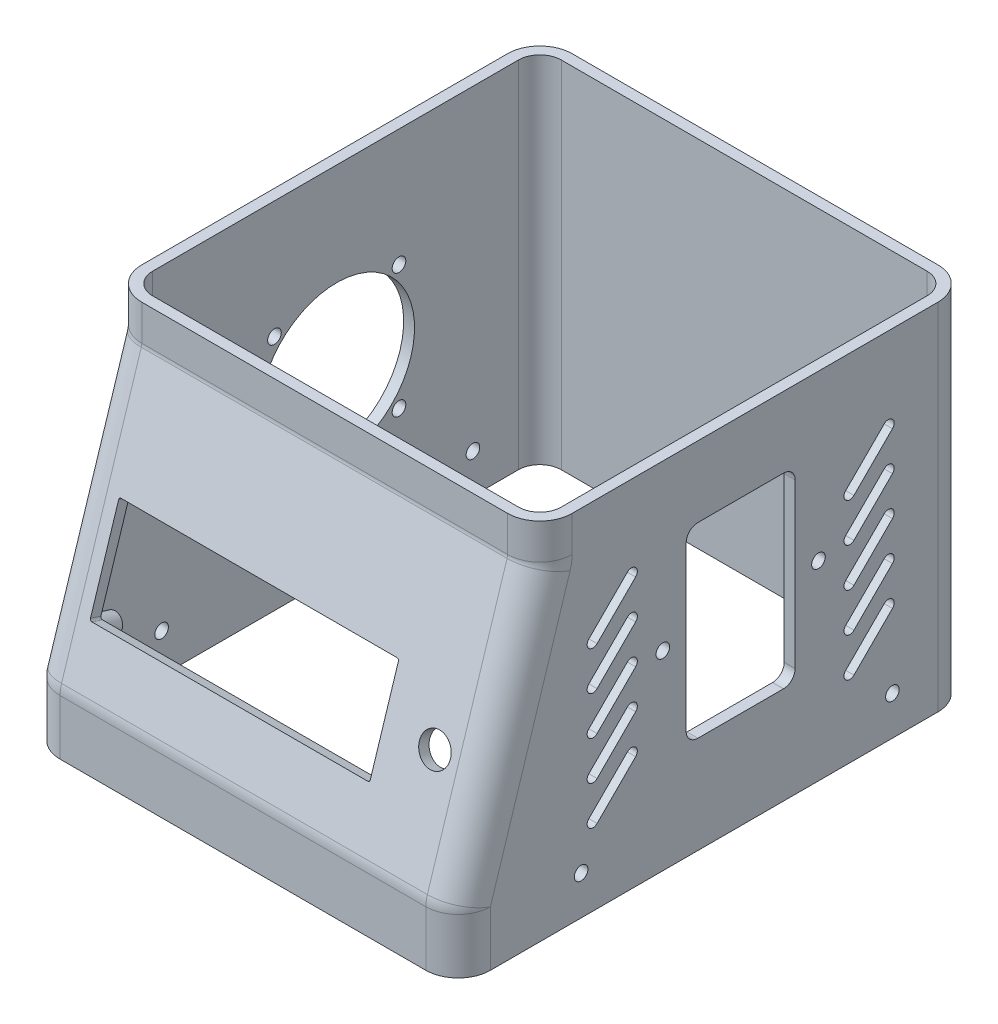
SolidWorks part; units mm, degrees
ref_plane "Front Plane" through (0, 0, 0) normal (0, 0, 1) x (1, 0, 0)
ref_plane "Top Plane" through (0, 0, 0) normal (0, 1, 0) x (1, 0, 0)
ref_plane "Right Plane" through (0, 0, 0) normal (1, 0, 0) x (0, 0, -1)
sketch "Sketch4" plane through (0, 0, 0) normal (1, 0, 0) x (0, 0, -1)
  line L0 (0, 0) -> (0, 15)
  line L1 (0, 15) -> (21, 81.2)
  line L2 (21, 81.2) -> (21, 91.2)
  line L3 (21, 91.2) -> (126, 91.2)
  line L4 (126, 91.2) -> (126, 0)
  line L5 (126, 0) -> (0, 0)
  dimension "D1" = 15
  dimension "D2" = 17.6
  dimension "D3" = 10
  dimension "D4" = 91.2
  dimension "D5" = 69.451
  dimension "D6" = 105
  dimension "D7" = 126
extrude "Boss-Extrude3" add sketch "Sketch4" along normal mid plane 105
fillet "Fillet3" radius 5.5 10 edges at (-52.5, 86.2, -21) (0, 81.2, -21) (52.5, 48.1, -10.5) (0, 15, 0) (-52.5, 48.1, -10.5) (-52.5, 7.5, 0) (52.5, 7.5, 0) (-52.5, 45.6, -126) (52.5, 45.6, -126) (52.5, 86.2, -21)
shell "Shell1" thickness 2.8
ref_plane "Plane1" through (0, 0, -73.5) normal (0, 0, 1) x (1, 0, 0)
sketch "Sketch6" plane through (0, 1.3714, 4.3233) normal (0, -0.3024, -0.9532) x (-1, 0, 0)
  line L0 (-27.45, 54.0493) -> (43.45, 54.0493)
  line L5 (-27.95, 53.5493) -> (-27.95, 29.6493)
  line L6 (-27.45, 29.1493) -> (43.45, 29.1493)
  line L7 (43.95, 53.5493) -> (43.95, 29.6493)
  line L8 (47, 15.1493) -> (-47, 15.1493) construction
  line L9 (-29.5, 57.5993) -> (45.5, 57.5993) construction
  line L10 (-29.5, 57.5993) -> (-29.5, 26.5993) construction
  line L11 (-29.5, 26.5993) -> (45.5, 26.5993) construction
  line L12 (45.5, 57.5993) -> (45.5, 26.5993) construction
  line L14 (47, 82.8974) -> (47, 15.1493) construction
  arc A0 (-27.95, 29.6493) -> (-27.45, 29.1493) centre (-27.45, 29.6493) ccw
  arc A1 (43.45, 29.1493) -> (43.95, 29.6493) centre (43.45, 29.6493) ccw
  arc A2 (43.95, 53.5493) -> (43.45, 54.0493) centre (43.45, 53.5493) ccw
  arc A3 (-27.45, 54.0493) -> (-27.95, 53.5493) centre (-27.45, 53.5493) ccw
  circle A4 centre (-29.5, 57.5993) radius 1.5 construction
  circle A5 centre (45.5, 57.5993) radius 1.5 construction
  circle A6 centre (45.5, 26.5993) radius 1.5 construction
  circle A7 centre (-29.5, 26.5993) radius 1.5 construction
  dimension "D3" = 0.5
  dimension "D10" = 3
  dimension "D1" = 14
  dimension "D2" = 1.5
  dimension "D4" = 24.9
  dimension "D5" = 71.9
  dimension "D6" = 75
  dimension "D7" = 31
  dimension "D8" = 3.55
  dimension "D9" = 3.1
  dimension "D11" = 3.55
  dimension "D12" = 2.55
extrude "Cut-Extrude1" cut sketch "Sketch6" against normal up to next
sketch "Sketch7" plane through (0, 1.3714, 4.3233) normal (0, -0.3024, -0.9532) x (-1, 0, 0)
  circle A4 centre (-29.5, 57.5993) radius 1.25
  circle A5 centre (-29.5, 26.5993) radius 1.25
  circle A6 centre (45.5, 26.5993) radius 1.25
  circle A7 centre (45.5, 57.5993) radius 1.25
  circle A8 centre (-29.5, 57.5993) radius 2.5
  circle A9 centre (45.5, 57.5993) radius 2.5
  circle A10 centre (45.5, 26.5993) radius 2.5
  circle A11 centre (-29.5, 26.5993) radius 2.5
  dimension "D1" = 5
  dimension "D2" = 2.5
extrude "Boss-Extrude4" add sketch "Sketch7" along normal offset from surface (5.7 mm away) 8.5 up to face at (-8, 41.8701, -5.5862)
sketch "Sketch8" plane through (0, 2.2181, 6.9922) normal (0, 0.3024, 0.9532) x (1, 0, 0)
  line L0 (27.95, 41.5993) -> (40.95, 41.5993) construction
  line L1 (27.95, 29.6493) -> (27.95, 53.5493) construction
  circle A0 centre (40.95, 41.5993) radius 4
  dimension "D1" = 8
  dimension "D2" = 13
extrude "Cut-Extrude2" cut sketch "Sketch8" against normal up to next
sketch "Sketch9" plane through (0, 0, -126) normal (0, 0, 1) x (1, 0, 0)
  line L0 (0, 0) -> (0, 91.2) construction
  line L1 (-40, 71) -> (22, 71) construction
  line L2 (-40, 71) -> (-40, 19) construction
  line L3 (-40, 19) -> (22, 19) construction
  line L4 (22, 71) -> (22, 19) construction
  line L5 (-44, 75) -> (26, 75)
  line L6 (-44, 75) -> (-44, 15)
  line L7 (-44, 15) -> (26, 15)
  line L8 (26, 75) -> (26, 15)
  line L9 (47, 0) -> (-47, 0) construction
  line L10 (47, 91.2) -> (-47, 91.2) construction
  dimension "D1" = 62
  dimension "D2" = 52
  dimension "D3" = 4
  dimension "D4" = 4
  dimension "D5" = 70
  dimension "D6" = 60
  dimension "D7" = 15
  dimension "D8" = 22
sketch "Sketch10" plane through (0, 0, -126) normal (0, 0, 1) x (1, 0, 0)
  circle A0 centre (-40, 19) radius 3
  circle A1 centre (-40, 71) radius 3
  circle A2 centre (22, 19) radius 3
  circle A3 centre (22, 71) radius 3
  circle A4 centre (-40, 19) radius 1.25
  circle A5 centre (-40, 71) radius 1.25
  circle A6 centre (22, 71) radius 1.25
  circle A7 centre (22, 19) radius 1.25
  dimension "D1" = 6
  dimension "D2" = 2.5
extrude "Boss-Extrude5" [suppressed] add sketch "Sketch10" along normal blind 7
sketch "Sketch11" plane through (-55.3, 0, 0) normal (-1, 0, 0) x (0, 0, 1)
  line L0 (-108.8, 10) -> (-28.8, 10) construction
  line L1 (-68.8, 10) -> (-68.8, 0) construction
  line L2 (-5.5, 0) -> (-120.5, 0) construction
  line L3 (-128.8, 0) -> (-128.8, 91.2) construction
  circle A0 centre (-108.8, 10) radius 1.75
  circle A1 centre (-28.8, 10) radius 1.75
  dimension "D1" = 3.5
  dimension "D2" = 80
  dimension "D3" = 60
  dimension "D4" = 10
extrude "Cut-Extrude3" cut sketch "Sketch11" against normal through all
chamfer "Chamfer1" [suppressed] distance 4 angle 45
sketch "Sketch12" plane through (55.3, 0, 0) normal (1, 0, 0) x (0, 0, -1)
  line L0 (5.5, 0) -> (120.5, 0) construction
  line L1 (55.8, 73) -> (83.8, 73)
  line L2 (55.8, 73) -> (55.8, 25)
  line L3 (55.8, 25) -> (83.8, 25)
  line L4 (83.8, 73) -> (83.8, 25)
  line L5 (128.8, 91.2) -> (128.8, 0) construction
  line L6 (69.8, 73) -> (69.8, 49) construction
  line L7 (69.8, 49) -> (55.8, 49) construction
  circle A0 centre (49.8, 49) radius 1.75
  circle A1 centre (89.8, 49) radius 1.75
  dimension "D5" = 40
  dimension "D6" = 3.5
  dimension "D1" = 25
  dimension "D2" = 45
  dimension "D3" = 28
  dimension "D4" = 48
extrude "Cut-Extrude4" cut sketch "Sketch12" against normal up to surface (2.8 mm away) up to face at (52.5, 10, -107.05)
ref_plane "Plane2" through (0, 79.2, 0) normal (0, 1, 0) x (1, 0, 0)
sketch "Sketch13" [suppressed] plane through (0, 78, 0) normal (0, 1, 0) x (1, 0, 0)
  line L0 (-47, 126) -> (47, 126)
  line L1 (-47, 126) -> (47, 126)
  line L2 (52.5, 120.5) -> (52.5, 26.5)
  line L3 (52.5, 120.5) -> (52.5, 26.5)
  line L4 (47, 21) -> (-47, 21)
  line L5 (47, 21) -> (-47, 21)
  line L6 (-52.5, 120.5) -> (-52.5, 26.5)
  line L7 (-52.5, 120.5) -> (-52.5, 26.5)
  line L8 (47, 26) -> (-47, 26)
  line L9 (-47.5, 120.5) -> (-47.5, 26.5)
  line L10 (-47, 121) -> (47, 121)
  line L11 (47.5, 120.5) -> (47.5, 26.5)
  line L12 (22, 126) -> (-40, 126)
  line L13 (-40, 126) -> (22, 126)
  line L15 (-40, 126) -> (22, 126)
  line L16 (22, 126) -> (-40, 126)
  arc A0 (52.5, 120.5) -> (47, 126) centre (47, 120.5) ccw
  arc A1 (52.5, 120.5) -> (47, 126) centre (47, 120.5) ccw
  arc A2 (47, 21) -> (52.5, 26.5) centre (47, 26.5) ccw
  arc A3 (47, 21) -> (52.5, 26.5) centre (47, 26.5) ccw
  arc A4 (-52.5, 26.5) -> (-47, 21) centre (-47, 26.5) ccw
  arc A5 (-52.5, 26.5) -> (-47, 21) centre (-47, 26.5) ccw
  arc A6 (-47, 126) -> (-52.5, 120.5) centre (-47, 120.5) ccw
  arc A7 (-47, 126) -> (-52.5, 120.5) centre (-47, 120.5) ccw
  arc A8 (-47.5, 26.5) -> (-47, 26) centre (-47, 26.5) ccw
  arc A9 (-47, 121) -> (-47.5, 120.5) centre (-47, 120.5) ccw
  arc A10 (47.5, 120.5) -> (47, 121) centre (47, 120.5) ccw
  arc A11 (47, 26) -> (47.5, 26.5) centre (47, 26.5) ccw
  dimension "D1" = 5
extrude "Boss-Extrude6" [suppressed] add sketch "Sketch13" against normal blind 3.5
chamfer "Chamfer2" [suppressed] distance 5 angle 60
sketch "Sketch15" [suppressed] plane through (0, 88, 0) normal (0, 1, 0) x (1, 0, 0)
  line L0 (0, 0) -> (0, 21) construction
  line L1 (-52.5, 78.5) -> (-5, 78.5)
  line L2 (-52.5, 78.5) -> (-52.5, 68.5)
  line L3 (-52.5, 68.5) -> (-5, 68.5)
  line L4 (52.5, 78.5) -> (52.5, 68.5)
  line L5 (-5, 126) -> (5, 126)
  line L6 (-5, 126) -> (-5, 78.5)
  line L7 (-5, 21) -> (5, 21)
  line L8 (5, 126) -> (5, 78.5)
  line L9 (52.5, 73.5) -> (-47.5, 73.5) construction
  line L10 (-47.5, 120.5) -> (-47.5, 26.5) construction
  line L14 (-5, 68.5) -> (-5, 21)
  line L15 (5, 78.5) -> (52.5, 78.5)
  line L16 (5, 68.5) -> (5, 21)
  line L17 (5, 68.5) -> (52.5, 68.5)
  line L18 (-52.5, 120.5) -> (-52.5, 26.5) construction
  line L19 (47, 126) -> (-47, 126) construction
  line L20 (52.5, 26.5) -> (52.5, 120.5) construction
  line L21 (52.5, 120.5) -> (52.5, 26.5) construction
  line L22 (-47, 21) -> (47, 21) construction
  point P41 (52.5, 73.5)
  dimension "D1" = 10
extrude "Cut-Extrude5" [suppressed] cut sketch "Sketch15" against normal blind 2
sketch "Sketch17" plane through (0, 1.3714, 4.3233) normal (0, -0.3024, -0.9532) x (-1, 0, 0)
  line L0 (-40.95, 41.5993) -> (-40.95, 61.5993) construction
  line L1 (-40.95, 41.5993) -> (-40.95, 29.5993) construction
  circle A0 centre (-40.95, 61.5993) radius 2.5
  circle A1 centre (-40.95, 29.5993) radius 2.5
  circle A2 centre (-40.95, 61.5993) radius 1.25
  circle A3 centre (-40.95, 29.5993) radius 1.25
  circle A6 centre (-29.5, 26.5993) radius 2.5 construction
  circle A7 centre (-29.5, 26.5993) radius 1.25 construction
  dimension "D1" = 32
  dimension "D2" = 12
extrude "Boss-Extrude7" add sketch "Sketch17" along normal blind 8.4
fillet "Fillet4" radius 3 4 edges at (53.9, 73, -55.8) (53.9, 73, -83.8) (53.9, 25, -83.8) (53.9, 25, -55.8)
sketch "Sketch18" plane through (-55.3, 0, 0) normal (-1, 0, 0) x (0, 0, 1)
  line L0 (-5.5, 0) -> (-120.5, 0) construction
  line L1 (-89.8, 29) -> (-57.8, 29) construction
  line L2 (-89.8, 29) -> (-89.8, 61) construction
  line L3 (-89.8, 61) -> (-57.8, 61) construction
  line L4 (-57.8, 29) -> (-57.8, 61) construction
  line L5 (-89.8, 29) -> (-57.8, 61) construction
  line L6 (-89.8, 61) -> (-57.8, 29) construction
  line L7 (-128.8, 0) -> (-128.8, 91.2) construction
  circle A0 centre (-73.8, 45) radius 20
  circle A1 centre (-89.8, 61) radius 1.75
  circle A2 centre (-57.8, 61) radius 1.75
  circle A3 centre (-57.8, 29) radius 1.75
  circle A4 centre (-89.8, 29) radius 1.75
  dimension "D1" = 40
  dimension "D2" = 3.5
  dimension "D3" = 32
  dimension "D4" = 45
  dimension "D5" = 55
extrude "Cut-Extrude6" cut sketch "Sketch18" against normal up to surface (2.8 mm away) up to face at (-52.5, 10, -107.05)
sketch "Sketch20" plane through (55.3, 0, 0) normal (1, 0, 0) x (0, 0, -1)
  line L0 (31.8503, 60.0503) -> (41.7497, 69.9497) construction
  line L1 (30.7896, 61.1109) -> (40.6891, 71.0104)
  line L2 (32.9109, 58.9896) -> (42.8104, 68.8891)
  line L4 (31.8503, 50.0503) -> (41.7497, 59.9497) construction
  line L7 (30.7896, 51.1109) -> (40.6891, 61.0104)
  line L11 (36.8, 65) -> (36.8, 0) construction
  line L12 (5.5, 0) -> (120.5, 0) construction
  line L13 (32.9109, 48.9896) -> (42.8104, 58.8891)
  line L14 (31.8503, 40.0503) -> (41.7497, 49.9497) construction
  line L15 (30.7896, 41.1109) -> (40.6891, 51.0104)
  line L16 (32.9109, 38.9896) -> (42.8104, 48.8891)
  line L18 (128.8, 91.2) -> (128.8, 0) construction
  line L19 (31.8503, 30.0503) -> (41.7497, 39.9497) construction
  line L20 (30.7896, 31.1109) -> (40.6891, 41.0104)
  line L21 (32.9109, 28.9896) -> (42.8104, 38.8891)
  line L22 (31.8503, 20.0503) -> (41.7497, 29.9497) construction
  line L23 (30.7896, 21.1109) -> (40.6891, 31.0104)
  line L24 (32.9109, 18.9896) -> (42.8104, 28.8891)
  line L25 (69.8, 73) -> (69.8, 91.2) construction
  line L26 (80.8, 73) -> (58.8, 73) construction
  line L27 (120.5, 91.2) -> (26.5, 91.2) construction
  line L28 (102.8, 65) -> (102.8, 0) construction
  line L29 (97.8503, 60.0503) -> (107.7497, 69.9497) construction
  line L30 (96.7896, 61.1109) -> (106.6891, 71.0104)
  line L31 (98.9109, 58.9896) -> (108.8104, 68.8891)
  line L32 (97.8503, 50.0503) -> (107.7497, 59.9497) construction
  line L33 (96.7896, 51.1109) -> (106.6891, 61.0104)
  line L34 (98.9109, 48.9896) -> (108.8104, 58.8891)
  line L35 (97.8503, 40.0503) -> (107.7497, 49.9497) construction
  line L36 (96.7896, 41.1109) -> (106.6891, 51.0104)
  line L37 (98.9109, 38.9896) -> (108.8104, 48.8891)
  line L38 (97.8503, 30.0503) -> (107.7497, 39.9497) construction
  line L39 (96.7896, 31.1109) -> (106.6891, 41.0104)
  line L40 (98.9109, 28.9896) -> (108.8104, 38.8891)
  line L41 (97.8503, 20.0503) -> (107.7497, 29.9497) construction
  line L42 (96.7896, 21.1109) -> (106.6891, 31.0104)
  line L43 (98.9109, 18.9896) -> (108.8104, 28.8891)
  arc A26 (30.7896, 61.1109) -> (32.9109, 58.9896) centre (31.8503, 60.0503) ccw
  arc A27 (42.8104, 68.8891) -> (40.6891, 71.0104) centre (41.7497, 69.9497) ccw
  arc A32 (30.7896, 51.1109) -> (32.9109, 48.9896) centre (31.8503, 50.0503) ccw
  arc A33 (42.8104, 58.8891) -> (40.6891, 61.0104) centre (41.7497, 59.9497) ccw
  arc A34 (30.7896, 41.1109) -> (32.9109, 38.9896) centre (31.8503, 40.0503) ccw
  arc A35 (42.8104, 48.8891) -> (40.6891, 51.0104) centre (41.7497, 49.9497) ccw
  arc A36 (30.7896, 31.1109) -> (32.9109, 28.9896) centre (31.8503, 30.0503) ccw
  arc A37 (42.8104, 38.8891) -> (40.6891, 41.0104) centre (41.7497, 39.9497) ccw
  arc A38 (30.7896, 21.1109) -> (32.9109, 18.9896) centre (31.8503, 20.0503) ccw
  arc A39 (42.8104, 28.8891) -> (40.6891, 31.0104) centre (41.7497, 29.9497) ccw
  arc A40 (96.7896, 61.1109) -> (98.9109, 58.9896) centre (97.8503, 60.0503) ccw
  arc A41 (108.8104, 68.8891) -> (106.6891, 71.0104) centre (107.7497, 69.9497) ccw
  arc A42 (96.7896, 51.1109) -> (98.9109, 48.9896) centre (97.8503, 50.0503) ccw
  arc A43 (108.8104, 58.8891) -> (106.6891, 61.0104) centre (107.7497, 59.9497) ccw
  arc A44 (96.7896, 41.1109) -> (98.9109, 38.9896) centre (97.8503, 40.0503) ccw
  arc A45 (108.8104, 48.8891) -> (106.6891, 51.0104) centre (107.7497, 49.9497) ccw
  arc A46 (96.7896, 31.1109) -> (98.9109, 28.9896) centre (97.8503, 30.0503) ccw
  arc A47 (108.8104, 38.8891) -> (106.6891, 41.0104) centre (107.7497, 39.9497) ccw
  arc A48 (96.7896, 21.1109) -> (98.9109, 18.9896) centre (97.8503, 20.0503) ccw
  arc A49 (108.8104, 28.8891) -> (106.6891, 31.0104) centre (107.7497, 29.9497) ccw
  point P2 (36.8, 65)
  point P12 (36.8, 55)
  point P19 (36.8, 45)
  point P30 (36.8, 25)
  point P31 (36.8, 35)
  point P51 (102.8, 65)
  point P59 (102.8, 55)
  point P66 (102.8, 45)
  point P73 (102.8, 35)
  point P80 (102.8, 25)
  dimension "D2" = 3
  dimension "D3" = 92
  dimension "D4" = 45
  dimension "D5" = 14
  dimension "D6" = 65
  dimension "D7" = 10
  dimension "D1" = 5
extrude "Cut-Extrude7" cut sketch "Sketch20" against normal up to surface (2.8 mm away) up to face at (52.5, 49, -88.05)
